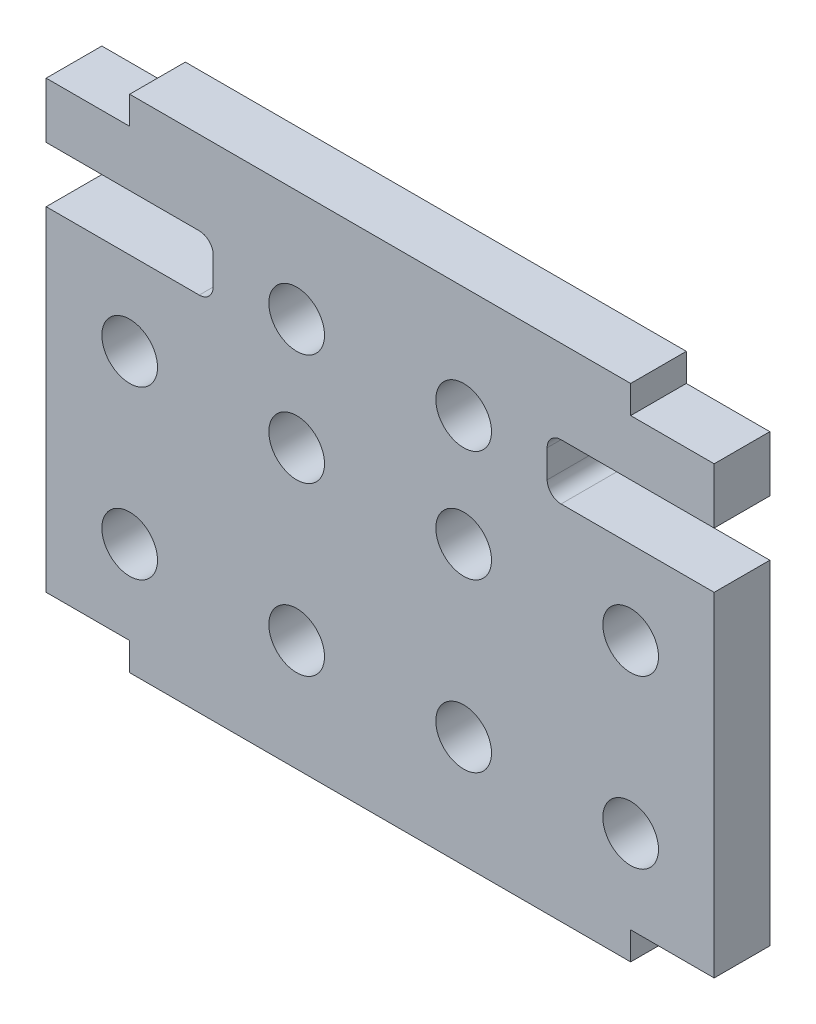
SolidWorks part; units mm, degrees
ref_plane "Alzado" through (0, 0, 0) normal (0, 0, 1) x (1, 0, 0)
ref_plane "Planta" through (0, 0, 0) normal (0, 1, 0) x (1, 0, 0)
ref_plane "Vista lateral" through (0, 0, 0) normal (1, 0, 0) x (0, 0, -1)
sketch "Model" plane through (0, 0, 0) normal (0, 0, 1) x (1, 0, 0)
  line L0 (105.8752, 202.0893) -> (105.8752, 205.0893)
  line L1 (105.8752, 199.0893) -> (105.8752, 181.0893)
  line L2 (110.3752, 205.0893) -> (105.8752, 205.0893)
  line L3 (110.3752, 181.0893) -> (105.8752, 181.0893)
  line L4 (110.3752, 179.5893) -> (110.3752, 181.0893)
  line L5 (137.3752, 179.5893) -> (110.3752, 179.5893)
  line L6 (137.3752, 181.0893) -> (137.3752, 179.5893)
  line L7 (141.8752, 181.0893) -> (137.3752, 181.0893)
  line L8 (137.3752, 205.0893) -> (141.8752, 205.0893)
  line L9 (137.3752, 206.5893) -> (137.3752, 205.0893)
  line L10 (110.3752, 206.5893) -> (137.3752, 206.5893)
  line L11 (110.3752, 205.0893) -> (110.3752, 206.5893)
  line L12 (114.1252, 199.0893) -> (105.8752, 199.0893)
  line L13 (114.1252, 202.0893) -> (105.8752, 202.0893)
  line L14 (114.8752, 201.3393) -> (114.8752, 199.8393)
  line L18 (133.6252, 202.0893) -> (141.8752, 202.0893)
  line L19 (133.6252, 199.0893) -> (141.8752, 199.0893)
  line L20 (132.8752, 199.8393) -> (132.8752, 201.3393)
  line L21 (141.8752, 199.0893) -> (141.8752, 181.0893)
  line L22 (141.8752, 205.0893) -> (141.8752, 202.0893)
  circle A0 centre (128.3752, 200.5893) radius 1.5
  circle A1 centre (119.3752, 200.5893) radius 1.5
  arc A2 (114.8752, 201.3393) -> (114.1252, 202.0893) centre (114.1252, 201.3393) ccw
  arc A3 (114.1252, 199.0893) -> (114.8752, 199.8393) centre (114.1252, 199.8393) ccw
  circle A4 centre (137.3752, 185.5893) radius 1.5
  circle A5 centre (128.3752, 185.5893) radius 1.5
  circle A6 centre (110.3752, 185.5893) radius 1.5
  circle A7 centre (119.3752, 185.5893) radius 1.5
  circle A8 centre (137.3752, 194.5893) radius 1.5
  circle A9 centre (128.3752, 194.5893) radius 1.5
  circle A10 centre (110.3752, 194.5893) radius 1.5
  circle A11 centre (119.3752, 194.5893) radius 1.5
  arc A14 (132.8752, 199.8393) -> (133.6252, 199.0893) centre (133.6252, 199.8393) ccw
  arc A15 (133.6252, 202.0893) -> (132.8752, 201.3393) centre (133.6252, 201.3393) ccw
extrude "Saliente-Extruir1" add sketch "Model" along normal blind 3
